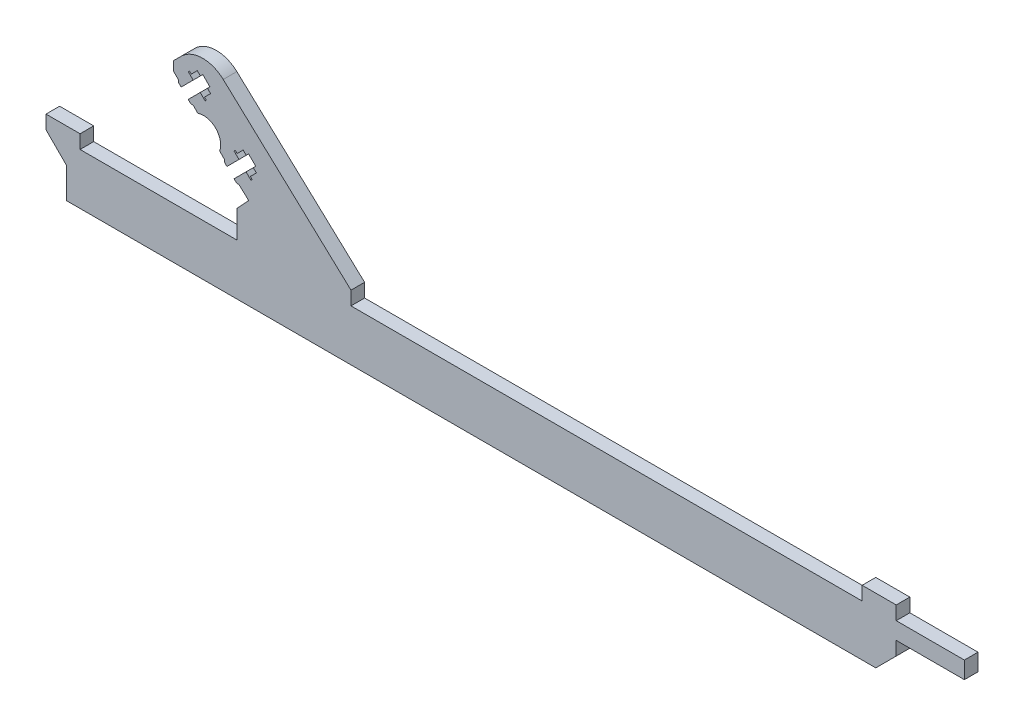
SolidWorks part; units mm, degrees
ref_plane "Front Plane" through (0, 0, 0) normal (0, 0, 1) x (1, 0, 0)
ref_plane "Top Plane" through (0, 0, 0) normal (0, 1, 0) x (1, 0, 0)
ref_plane "Right Plane" through (0, 0, 0) normal (1, 0, 0) x (0, 0, -1)
sketch "Sketch1" plane through (0, 0, 0) normal (0, 0, 1) x (1, 0, 0)
  line L0 (-193.5, 5) -> (-193.5, 13.029)
  line L1 (0, 0) -> (20, 0)
  line L2 (-243.5, -1) -> (-249.5, 5)
  line L3 (0, 5) -> (20, 5)
  line L4 (20, 0) -> (20, 5)
  line L5 (-10, 5) -> (-160, 5)
  line L6 (0, 0) -> (0, -10)
  line L7 (0, -10) -> (-243.5, -10)
  line L8 (-243.5, -1) -> (-243.5, -10)
  line L9 (-193.5, 5) -> (-239.5, 5)
  line L10 (-249.5, 5) -> (-249.5, 9)
  line L11 (-249.5, 9) -> (-239.5, 9)
  line L12 (-239.5, 5) -> (-239.5, 9)
  line L13 (-210.2093, 33.2093) -> (-202.446, 41.0024) construction
  line L14 (-212.0269, 41.3376) -> (-212.0269, 38.5624)
  line L15 (-209.7892, 43.5753) -> (-212.0269, 41.3376)
  line L16 (-160, 5) -> (-160, 9)
  line L17 (-197.4926, 43.8039) -> (-160, 9)
  line L18 (0, 5) -> (0, 9)
  line L19 (0, 9) -> (-10, 9)
  line L20 (-10, 5) -> (-10, 9)
  line L21 (-188.9976, 27.554) -> (-196.7758, 19.7758) construction
  line L26 (-190.0284, 16.7689) -> (-193.5, 13.029)
  line L27 (-220, 30) -> (-210, 30) construction
  line L28 (-220, 30) -> (-220, 10) construction
  line L29 (-200, 30) -> (-200, 10) construction
  line L30 (-220, 10) -> (-200, 10) construction
  line L31 (-220, 30) -> (-200, 10) construction
  line L32 (-200, 30) -> (-220, 10) construction
  line L33 (-210, 20) -> (-210, 30) construction
  line L34 (-207, 29.3) -> (-207, 29) construction
  line L35 (-206.5, 28.5) -> (-204, 28.5) construction
  line L36 (-204, 28.5) -> (-204, 27.0607) construction
  line L37 (-204, 27.0607) -> (-206.2641, 24.7966) construction
  line L38 (-206.2641, 24.7966) -> (-210, 24.7966) construction
  line L39 (-206.8, 29.5) -> (-206.7, 29.5) construction
  line L40 (-206.5, 29.7) -> (-206.5, 29.8) construction
  line L41 (-206.3, 30) -> (-201.5, 30) construction
  line L42 (-200, 23.7) -> (-200, 28.5) construction
  line L43 (-200.3, 23.5) -> (-200.2, 23.5) construction
  line L44 (-200.5, 23.2) -> (-200.5, 23.3) construction
  line L45 (-205.2034, 23.7359) -> (-205.2034, 20) construction
  line L46 (-202.9393, 26) -> (-205.2034, 23.7359) construction
  line L47 (-201.5, 26) -> (-202.9393, 26) construction
  line L48 (-201.5, 23.5) -> (-201.5, 26) construction
  line L49 (-200.7, 23) -> (-201, 23) construction
  line L50 (-215.1413, 35.3129) -> (-212.3129, 38.1413) construction
  line L51 (-215.1413, 35.3129) -> (-208.1056, 28.2772) construction
  line L52 (-212.3129, 38.1413) -> (-205.2772, 31.1056) construction
  line L53 (-208.1056, 28.2772) -> (-205.2772, 31.1056) construction
  line L54 (-215.1413, 35.3129) -> (-205.2772, 31.1056) construction
  line L55 (-212.3129, 38.1413) -> (-208.1056, 28.2772) construction
  line L56 (-210.2093, 33.2093) -> (-206.6914, 29.6914) construction
  line L58 (-209.853, 35.6814) -> (-206.3174, 39.2169)
  line L59 (-206.3174, 39.2169) -> (-207.7493, 40.6488)
  line L60 (-207.7493, 40.6488) -> (-207.3958, 41.0024)
  line L61 (-207.3958, 41.0024) -> (-206.8655, 40.4721)
  line L62 (-206.8655, 40.4721) -> (-205.0977, 42.2398)
  line L63 (-205.0977, 42.2398) -> (-204.1961, 41.3383)
  line L64 (-204.1961, 41.3383) -> (-203.489, 42.0454)
  line L65 (-203.489, 42.0454) -> (-201.4031, 39.9594)
  line L66 (-209.853, 35.6814) -> (-210.5778, 36.4062)
  line L67 (-210.5778, 36.4062) -> (-210.5778, 37.1133)
  line L68 (-210.5778, 37.1133) -> (-212.0269, 38.5624)
  line L69 (-206.3351, 32.8707) -> (-204.9209, 31.4565)
  line L70 (-207.0422, 32.8707) -> (-206.3351, 32.8707)
  line L71 (-207.767, 33.5955) -> (-207.0422, 32.8707)
  line L72 (-207.767, 33.5955) -> (-204.2315, 37.131)
  line L73 (-204.2315, 37.131) -> (-202.7996, 35.6991)
  line L74 (-202.7996, 35.6991) -> (-202.446, 36.0526)
  line L75 (-202.446, 36.0526) -> (-202.9764, 36.583)
  line L76 (-202.9764, 36.583) -> (-201.2086, 38.3507)
  line L77 (-201.2086, 38.3507) -> (-202.1102, 39.2523)
  line L78 (-202.1102, 39.2523) -> (-201.4031, 39.9594)
  line L79 (-197.1293, 23.6649) -> (-198.5435, 25.0791)
  line L80 (-197.1293, 22.9578) -> (-197.1293, 23.6649)
  line L81 (-196.4045, 22.233) -> (-197.1293, 22.9578)
  line L82 (-196.4045, 22.233) -> (-192.869, 25.7685)
  line L83 (-192.869, 25.7685) -> (-194.3009, 27.2004)
  line L84 (-194.3009, 27.2004) -> (-193.9474, 27.554)
  line L85 (-193.9474, 27.554) -> (-193.417, 27.0236)
  line L86 (-193.417, 27.0236) -> (-191.6493, 28.7914)
  line L87 (-191.6493, 28.7914) -> (-190.7477, 27.8898)
  line L88 (-190.7477, 27.8898) -> (-190.0406, 28.5969)
  line L89 (-187.9546, 26.511) -> (-190.0406, 28.5969)
  line L90 (-188.6617, 25.8039) -> (-187.9546, 26.511)
  line L91 (-187.7602, 24.9023) -> (-188.6617, 25.8039)
  line L92 (-189.5279, 23.1345) -> (-187.7602, 24.9023)
  line L93 (-188.9976, 22.6042) -> (-189.5279, 23.1345)
  line L94 (-189.3512, 22.2507) -> (-188.9976, 22.6042)
  line L95 (-190.7831, 23.6826) -> (-189.3512, 22.2507)
  line L96 (-194.3186, 20.147) -> (-190.7831, 23.6826)
  line L97 (-194.3186, 20.147) -> (-193.5938, 19.4222)
  line L98 (-193.5938, 19.4222) -> (-192.8867, 19.4222)
  line L99 (-192.8867, 19.4222) -> (-190.0284, 16.7689)
  arc A0 (-200, 28.5) -> (-201.5, 30) centre (-201.5, 28.5) ccw construction
  arc A1 (-206.5, 29.7) -> (-206.7, 29.5) centre (-206.7, 29.7) cw construction
  arc A2 (-206.8, 29.5) -> (-207, 29.3) centre (-206.8, 29.3) ccw construction
  arc A3 (-207, 29) -> (-206.5, 28.5) centre (-206.5, 29) ccw construction
  arc A4 (-206.3, 30) -> (-206.5, 29.8) centre (-206.3, 29.8) ccw construction
  arc A5 (-200, 23.7) -> (-200.2, 23.5) centre (-200.2, 23.7) cw construction
  arc A6 (-201, 23) -> (-201.5, 23.5) centre (-201, 23.5) cw construction
  arc A7 (-200.5, 23.2) -> (-200.7, 23) centre (-200.7, 23.2) cw construction
  arc A8 (-200.3, 23.5) -> (-200.5, 23.3) centre (-200.3, 23.3) ccw construction
  arc A9 (-197.4926, 43.8039) -> (-209.7892, 43.5753) centre (-203.5222, 37.3084) ccw
  arc A10 (-198.5435, 25.0791) -> (-204.9209, 31.4565) centre (-203.2123, 26.7877) ccw
  point P28 (-210, 20)
  point P71 (-210.2093, 33.2093)
  point P101 (-202.446, 41.0024)
  dimension "D21" = 0.2
  dimension "D24" = 0.5
  dimension "D26" = 1.5
  dimension "D1" = 243.5
  dimension "D2" = 20
  dimension "D3" = 5
  dimension "D4" = 4
  dimension "D5" = 10
  dimension "D6" = 180
  dimension "D7" = 10
  dimension "D8" = 6
  dimension "D9" = 6
  dimension "D10" = 2.95
  dimension "D11" = 7
  dimension "D12" = 5.5
  dimension "D13" = 5
  dimension "D14" = 50
  dimension "D18" = 20
  dimension "D19" = 43.5
  dimension "D20" = 25
  dimension "D22" = 3
  dimension "D23" = 1.5
  dimension "D25" = 0.5
  dimension "D27" = 20
  dimension "D28" = 4
  dimension "D29" = 0.75
  dimension "D30" = 0.5
  dimension "D31" = 0.5
  dimension "D32" = 4
  dimension "D33" = 9.95
  dimension "D34" = 0.5
  dimension "D36" = 0.5
  dimension "D37" = 2.5
  dimension "D38" = 1
  dimension "D42" = 12
extrude "Boss-Extrude1" add sketch "Sketch1" along normal blind 4
chamfer "Chamfer1" distance 6 angle 45 1 edges at (0, -10, 2)
sketch "Sketch2" plane through (-80.7218, -80.7218, 0) normal (-0.7071, -0.7071, 0) x (0, 0, 1)
  line L0 (4, 173.619) -> (0, 173.619) construction
  line L1 (0, 172.1035) -> (4, 172.1035) construction
  line L2 (4, 179.9587) -> (4, 171.4734) construction
  line L3 (0, 179.9587) -> (0, 171.4734) construction
  line L4 (0, 153.1212) -> (4, 153.1212) construction
  circle A0 centre (2, 172.1035) radius 1.5156 construction
  circle A1 centre (2, 172.1035) radius 0.3573
  circle A2 centre (2, 153.1212) radius 0.3573
  circle A3 centre (2, 153.1212) radius 1.5444 construction
extrude "Cut-Extrude1" cut sketch "Sketch2" against normal blind 1
